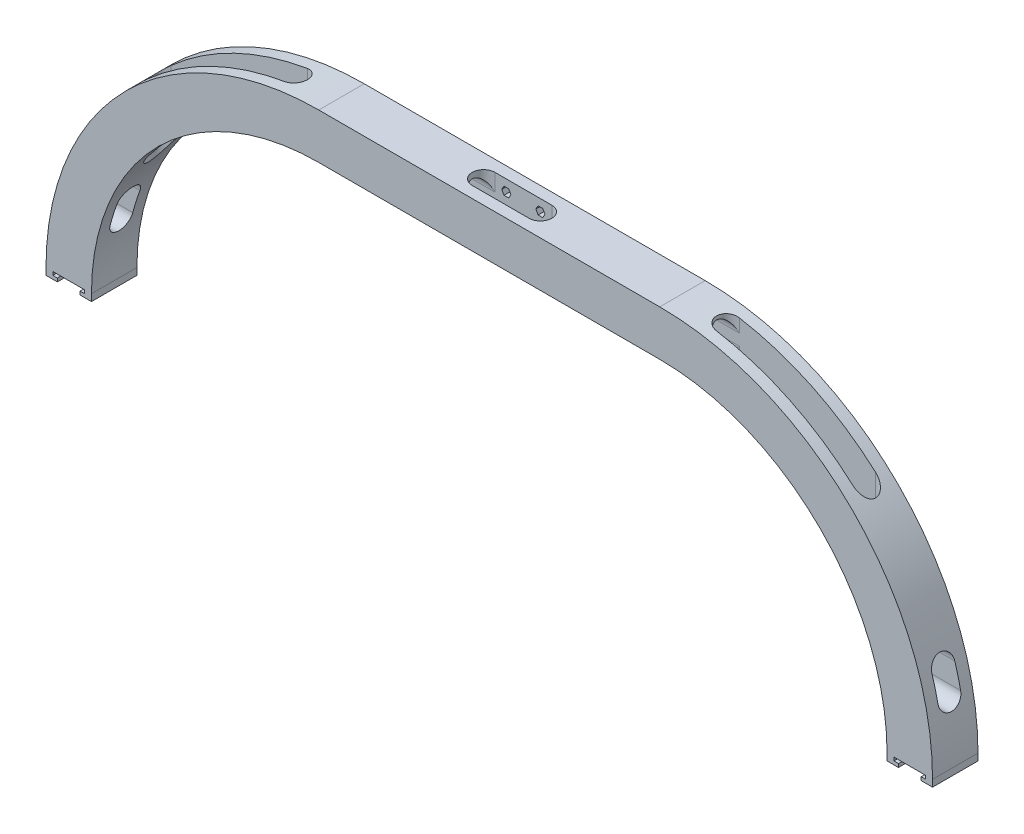
SolidWorks part; units mm, degrees
ref_plane "Ebene vorne" through (0, 0, 0) normal (0, 0, 1) x (1, 0, 0)
ref_plane "Ebene oben" through (0, 0, 0) normal (0, 1, 0) x (1, 0, 0)
ref_plane "Ebene rechts" through (0, 0, 0) normal (1, 0, 0) x (0, 0, -1)
ref_plane "Ebene1" through (0, 0, 0) normal (0, 0, 1) x (1, 0, 0)
ref_plane "Ebene2" through (0, 0, 0) normal (0, 1, 0) x (1, 0, 0)
ref_plane "Ebene3" through (0, 0, 0) normal (1, 0, 0) x (0, 0, -1)
sketch "Skizze1" plane through (0, 0, 0) normal (0, 0, 1) x (1, 0, 0)
  line L0 (-150, 600) -> (150, 600)
  line L1 (-150, 400) -> (150, 400)
  line L2 (55, 0) -> (-55, 0) construction
  line L3 (0, -559.102) -> (0, 559.102) construction
  line L4 (-1520.6314, 0) -> (1520.6314, 0) construction
  line L5 (-350, 200) -> (-550, 200)
  line L6 (350, 200) -> (550, 200)
  line L7 (-500, 393.6492) -> (-500, 200)
  line L8 (-500, 200) -> (-550, 200)
  line L9 (500, 200) -> (550, 200)
  line L10 (500, 393.6492) -> (500, 200)
  arc A2 (-550, 200) -> (-150, 600) centre (-150, 200) cw
  arc A3 (-350, 200) -> (-150, 400) centre (-150, 200) cw
  arc A6 (550, 200) -> (150, 600) centre (150, 200) ccw
  arc A7 (350, 200) -> (150, 400) centre (150, 200) ccw
  arc A8 (-550, 200) -> (-500, 393.6492) centre (-150, 200) cw
  arc A9 (550, 200) -> (500, 393.6492) centre (150, 200) ccw
  point P6 (0, 600)
  point P9 (0, 400)
  point P14 (0, 0)
  dimension "D5" = 200
  dimension "D1" = 600
  dimension "D2" = 200
  dimension "D3" = 300
  dimension "D4" = 150
extrude "Aufsatz-Linear austragen1" add sketch "Skizze1" along normal blind 150 contours A7 L6 L10 A6 L0 A2 L7 L5 A3 L1
sketch "Skizze2" plane through (0, 200, 0) normal (0, -1, 0) x (1, 0, 0)
  line L2 (350, 150) -> (500, 150) construction
  line L3 (350, 150) -> (350, 0) construction
  line L4 (-350, 150) -> (-350, 0) construction
  line L5 (-350, 150) -> (-500, 150) construction
  circle A0 centre (-370, 130) radius 5
  circle A1 centre (370, 130) radius 5
  point P8 (0, 0)
  dimension "D3" = 10
  dimension "D1" = 20
  dimension "D2" = 20
  dimension "D4" = 20
  dimension "D5" = 20
ref_plane "Ebene4" through (0, 600, 0) normal (0, 1, 0) x (1, 0, 0)
sketch "Skizze3" plane through (0, 600, 0) normal (0, 1, 0) x (1, 0, 0)
  line L0 (-25, -130) -> (25, -130) construction
  line L1 (-25, -120) -> (25, -120)
  line L2 (-25, -140) -> (25, -140)
  line L3 (0, -559.102) -> (0, 559.102) construction
  line L4 (-150, -150) -> (150, -150) construction
  arc A0 (-25, -120) -> (-25, -140) centre (-25, -130) ccw
  arc A1 (25, -140) -> (25, -120) centre (25, -130) ccw
  point P2 (0, -130)
  dimension "D1" = 50
  dimension "D2" = 10
  dimension "D3" = 20
sketch "Skizze4" plane through (0, 600, 0) normal (0, 1, 0) x (1, 0, 0)
  line L0 (-310, -130) -> (-190, -130) construction
  line L1 (-310, -120) -> (-190, -120)
  line L2 (-310, -140) -> (-190, -140)
  line L3 (190, -130) -> (310, -130) construction
  line L4 (190, -120) -> (310, -120)
  line L5 (190, -140) -> (310, -140)
  line L8 (-500, -150) -> (-150, -150) construction
  line L9 (150, -150) -> (500, -150) construction
  line L10 (0, -559.102) -> (0, 559.102) construction
  arc A0 (-310, -120) -> (-310, -140) centre (-310, -130) ccw
  arc A1 (-190, -140) -> (-190, -120) centre (-190, -130) ccw
  arc A2 (190, -120) -> (190, -140) centre (190, -130) ccw
  arc A3 (310, -140) -> (310, -120) centre (310, -130) ccw
  point P4 (-250, -130)
  point P9 (250, -130)
  dimension "D1" = 10
  dimension "D2" = 10
  dimension "D3" = 20
  dimension "D4" = 20
  dimension "D5" = 250
  dimension "D6" = 250
extrude "Schnitt-Linear austragen2" cut sketch "Skizze4" along normal through all and the other way through all
ref_plane "Ebene5" through (-190, 0, 0) normal (-1, 0, 0) x (0, 0, 1)
sketch "Skizze5" plane through (-190, 0, 0) normal (-1, 0, 0) x (0, 0, 1)
  line L0 (130, 425) -> (130, 415) construction
  line L1 (140, 425) -> (140, 415)
  line L2 (120, 425) -> (120, 415)
  line L3 (303.4057, 600) -> (-303.4057, 600) construction
  line L6 (150, 393.6492) -> (150, 600) construction
  arc A0 (140, 425) -> (120, 425) centre (130, 425) ccw
  arc A1 (120, 415) -> (140, 415) centre (130, 415) ccw
  point P2 (130, 420)
  point P7 (0, 0)
  point P11 (0, 0)
  dimension "D1" = 20
  dimension "D3" = 180
extrude "Schnitt-Linear austragen7" cut sketch "Skizze5" against normal up to next
extrude "Schnitt-Linear austragen8" cut sketch "Skizze3" against normal blind 180
sketch "Skizze9" plane through (0, 0, 0) normal (0, 0, -1) x (-1, 0, 0)
  line L0 (150, 600) -> (-150, 600) construction
  line L1 (-12.9793, 426.5) -> (-10.9585, 430)
  line L2 (-10.9585, 430) -> (-12.9793, 433.5)
  line L3 (-12.9793, 433.5) -> (-17.0207, 433.5)
  line L4 (-17.0207, 433.5) -> (-19.0415, 430)
  line L5 (-19.0415, 430) -> (-17.0207, 426.5)
  line L6 (-17.0207, 426.5) -> (-12.9793, 426.5)
  line L7 (0, 559.102) -> (0, -559.102) construction
  line L8 (17.0207, 426.5) -> (12.9793, 426.5)
  line L9 (19.0415, 430) -> (17.0207, 426.5)
  line L10 (17.0207, 433.5) -> (19.0415, 430)
  line L11 (12.9793, 433.5) -> (17.0207, 433.5)
  line L12 (10.9585, 430) -> (12.9793, 433.5)
  line L13 (12.9793, 426.5) -> (10.9585, 430)
  line L14 (150, 400) -> (-150, 400) construction
  line L15 (-12.9793, 406.5) -> (-10.9585, 410)
  line L16 (-10.9585, 410) -> (-12.9793, 413.5)
  line L17 (-12.9793, 413.5) -> (-17.0207, 413.5)
  line L18 (-17.0207, 413.5) -> (-19.0415, 410)
  line L19 (-19.0415, 410) -> (-17.0207, 406.5)
  line L20 (-17.0207, 406.5) -> (-12.9793, 406.5)
  line L21 (17.0207, 406.5) -> (12.9793, 406.5)
  line L22 (19.0415, 410) -> (17.0207, 406.5)
  line L23 (17.0207, 413.5) -> (19.0415, 410)
  line L24 (12.9793, 413.5) -> (17.0207, 413.5)
  line L25 (10.9585, 410) -> (12.9793, 413.5)
  line L26 (12.9793, 406.5) -> (10.9585, 410)
  circle A0 centre (-15, 430) radius 3.5 construction
  circle A1 centre (-15, 410) radius 3.5 construction
  dimension "D2" = 7
  dimension "D4" = 7
  dimension "D1" = 20
  dimension "D3" = 15
  dimension "D5" = 15
  dimension "D6" = 10
sketch "Skizze11" plane through (0, 0, 0) normal (0, 0, 1) x (1, 0, 0)
  line L0 (350, 200) -> (360, 200)
  line L1 (350, 200) -> (500, 200) construction
  line L2 (390, 200) -> (380, 200)
  line L3 (350, 200) -> (350, 194)
  line L4 (350, 194) -> (360, 194)
  line L5 (360, 194) -> (360, 200)
  line L6 (390, 200) -> (390, 194)
  line L7 (390, 194) -> (380, 194)
  line L8 (380, 194) -> (380, 200)
  line L10 (360, 197) -> (356, 197)
  line L11 (360, 197) -> (360, 200)
  line L12 (360, 200) -> (356, 200)
  line L13 (356, 197) -> (356, 200)
  line L14 (380, 197) -> (384, 197)
  line L15 (380, 197) -> (380, 200)
  line L16 (380, 200) -> (384, 200)
  line L17 (384, 197) -> (384, 200)
  dimension "D1" = 10
  dimension "D2" = 6
  dimension "D3" = 4
  dimension "D4" = 4
  dimension "D5" = 10
  dimension "D6" = 20
extrude "Aufsatz-Linear austragen2" add sketch "Skizze11" along normal up to surface (150 mm away) contours L10 L13 L0 L3 L4 L5 | L17 L14 L8 L7 L6 L2 up to face at (0, 376.5636, 150)
sketch "Skizze15" plane through (0, 600, 0) normal (0, 1, 0) x (1, 0, 0)
  line L0 (-397.1358, 0) -> (397.1358, 0) construction
  line L1 (-657.9131, 0) -> (732.809, 0)
  line L2 (-657.9131, 0) -> (-657.9131, -110)
  line L3 (-657.9131, -110) -> (732.809, -110)
  line L4 (732.809, 0) -> (732.809, -110)
  dimension "D1" = 110
extrude "Schnitt-Linear austragen16" cut sketch "Skizze15" against normal blind 1000
ref_plane "Ebene8" through (0, 194, 0) normal (0, -1, 0) x (-1, 0, 0)
ref_plane "Ebene9" through (0, 0, 150) normal (0, 0, 1) x (1, 0, 0)
sketch "Skizze17" plane through (0, 0, 150) normal (0, 0, 1) x (1, 0, 0)
  line L0 (-350, 200) -> (-390, 200)
  line L1 (-350, 200) -> (-500, 200) construction
  line L2 (-150, 440) -> (150, 440)
  line L3 (0, -559.102) -> (0, 559.102) construction
  line L4 (-150, 400) -> (150, 400) construction
  line L5 (350, 200) -> (390, 200)
  line L6 (390, 200) -> (500, 200) construction
  line L7 (-390, 200) -> (-728.9046, 200)
  line L8 (390, 200) -> (649.827, 200)
  arc A0 (-390, 200) -> (-150, 440) centre (-150, 200) cw
  arc A1 (390, 200) -> (150, 440) centre (150, 200) ccw
  arc A2 (-728.9046, 200) -> (649.827, 200) centre (-39.5388, 200) cw
  point P3 (0, 0)
  point P8 (0, 440)
  dimension "D1" = 300
  dimension "D2" = 40
extrude "Schnitt-Linear austragen22" cut sketch "Skizze17" against normal blind 200 contours A2 L7 A0 L2 A1 L8
sketch "Skizze18" plane through (0, 0, 150) normal (0, 0, 1) x (1, 0, 0)
  line L0 (-390, 200) -> (-369.5579, 200)
  line L1 (-350, 200) -> (-390, 200) construction
  line L2 (-369.5579, 200) -> (-369.5579, 296.9244)
  line L3 (-369.5579, 296.9244) -> (-580.7276, 200)
  line L4 (-580.7276, 200) -> (-390, 200)
  line L5 (0, -559.102) -> (0, 559.102) construction
  line L6 (369.5579, 296.9244) -> (580.7276, 200)
  line L7 (369.5579, 200) -> (369.5579, 296.9244)
  line L8 (390, 200) -> (369.5579, 200)
  line L9 (580.7276, 200) -> (390, 200)
  arc A0 (-150, 440) -> (-390, 200) centre (-150, 200) ccw construction
extrude "Schnitt-Linear austragen27" cut sketch "Skizze9" against normal up to surface (120 mm away) up to face at (0, 406.9985, 120)
ref_plane "Ebene13" through (-190, 415, 140) normal (-0.7071, 0.7071, 0) x (0.7071, 0.7071, 0)
extrude "Schnitt-Linear austragen28" cut sketch "Skizze2" against normal blind 10
sketch "Skizze21" plane through (0, 0, 150) normal (0, 0, 1) x (1, 0, 0)
  line L1 (-390, 200) -> (-380, 200)
  line L2 (-390, 200) -> (-390, 194)
  line L3 (-390, 194) -> (-380, 194)
  line L4 (-380, 200) -> (-380, 194)
  line L5 (-350, 200) -> (-360, 200)
  line L6 (-350, 200) -> (-350, 194)
  line L7 (-350, 194) -> (-360, 194)
  line L8 (-360, 200) -> (-360, 194)
  line L9 (-380, 200) -> (-384, 200)
  line L10 (-380, 200) -> (-380, 197)
  line L11 (-380, 197) -> (-384, 197)
  line L12 (-384, 200) -> (-384, 197)
  line L13 (-360, 200) -> (-356, 200)
  line L14 (-360, 200) -> (-360, 197)
  line L15 (-360, 197) -> (-356, 197)
  line L16 (-356, 200) -> (-356, 197)
  dimension "D1" = 10
  dimension "D2" = 20
  dimension "D3" = 4
  dimension "D4" = 4
  dimension "D5" = 6
  dimension "D6" = 6
  dimension "D7" = 3
  dimension "D8" = 3
extrude "Aufsatz-Linear austragen3" add sketch "Skizze21" against normal blind 40 contours L12 L1 L2 L3 L4 L11 | L5 L16 L15 L8 L7 L6
sketch "Skizze22" plane through (-190, 0, 0) normal (-1, 0, 0) x (0, 0, 1)
  line L0 (130, 270) -> (130, 250) construction
  line L1 (140, 270) -> (140, 250)
  line L2 (120, 270) -> (120, 250)
  line L3 (150, 200) -> (110, 200) construction
  line L5 (150, 200) -> (150, 400) construction
  arc A0 (140, 270) -> (120, 270) centre (130, 270) ccw
  arc A1 (120, 250) -> (140, 250) centre (130, 250) ccw
  point P2 (130, 260)
  point P9 (0, 0)
  dimension "D1" = 60
  dimension "D2" = 10
  dimension "D3" = 20
extrude "Schnitt-Linear austragen29" cut sketch "Skizze22" along normal blind 200
ref_plane "Ebene14" through (150, 0, 0) normal (1, 0, 0) x (0, 0, -1)
sketch "Skizze23" plane through (150, 0, 0) normal (1, 0, 0) x (0, 0, -1)
  line L0 (-130, 270) -> (-130, 250) construction
  line L1 (-120, 270) -> (-120, 250)
  line L2 (-140, 270) -> (-140, 250)
  line L3 (-150, 200) -> (-110, 200) construction
  line L5 (-110, 200) -> (-110, 400) construction
  arc A0 (-120, 270) -> (-140, 270) centre (-130, 270) ccw
  arc A1 (-140, 250) -> (-120, 250) centre (-130, 250) ccw
  point P2 (-130, 260)
  point P9 (0, 0)
  dimension "D1" = 60
  dimension "D2" = 20
extrude "Schnitt-Linear austragen30" cut sketch "Skizze23" along normal blind 300
